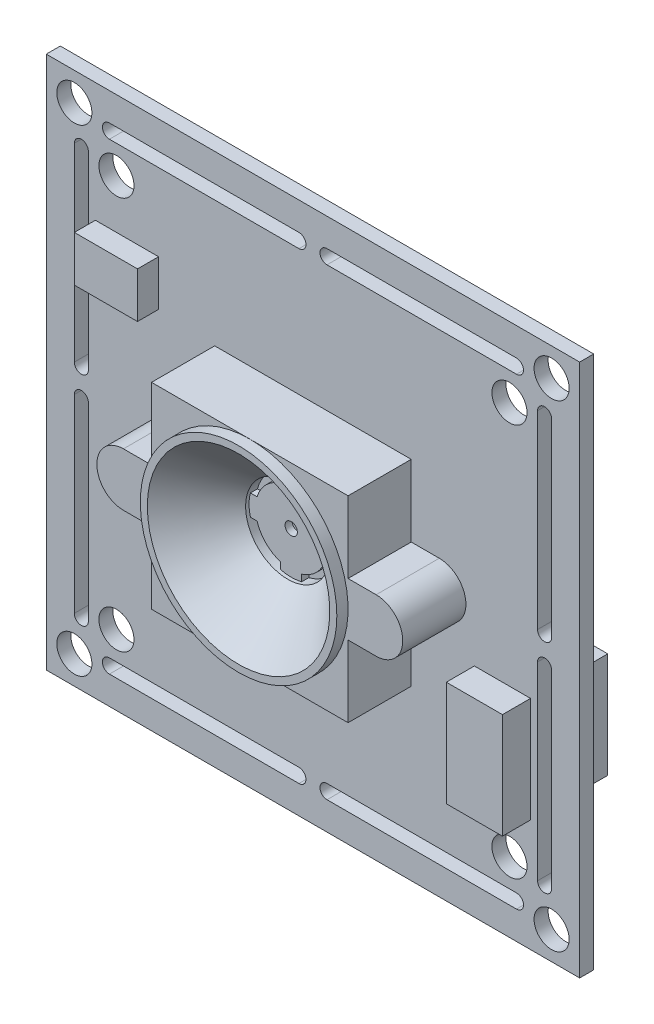
SolidWorks part; units mm, degrees
ref_plane "Front Plane" through (0, 0, 0) normal (0, 0, 1) x (1, 0, 0)
ref_plane "Top Plane" through (0, 0, 0) normal (0, 1, 0) x (1, 0, 0)
ref_plane "Right Plane" through (0, 0, 0) normal (1, 0, 0) x (0, 0, -1)
sketch "ｽｹｯﾁ1" plane through (0, 0, 0) normal (0, 0, 1) x (1, 0, 0)
  line L0 (1, 16.5) -> (14.5, 16.5) construction
  line L1 (-19, -19) -> (19, -19)
  line L2 (-19, -19) -> (-19, 19)
  line L3 (-19, 19) -> (19, 19)
  line L4 (19, -19) -> (19, 19)
  line L5 (-19, -19) -> (19, 19) construction
  line L6 (-19, 19) -> (19, -19) construction
  line L7 (1, 17) -> (14.5, 17)
  line L8 (1, 16) -> (14.5, 16)
  line L9 (0, 0) -> (0, 25.3594) construction
  line L10 (-1, 16.5) -> (-14.5, 16.5) construction
  line L11 (-1, 17) -> (-14.5, 17)
  line L12 (-1, 16) -> (-14.5, 16)
  line L13 (16.5, -1) -> (16.5, -14.5) construction
  line L14 (17, -1) -> (17, -14.5)
  line L15 (16, -1) -> (16, -14.5)
  line L16 (16.5, 1) -> (16.5, 14.5) construction
  line L17 (17, 1) -> (17, 14.5)
  line L18 (16, 1) -> (16, 14.5)
  line L19 (-1, -16.5) -> (-14.5, -16.5) construction
  line L20 (-1, -17) -> (-14.5, -17)
  line L21 (-1, -16) -> (-14.5, -16)
  line L22 (1, -16.5) -> (14.5, -16.5) construction
  line L23 (1, -17) -> (14.5, -17)
  line L24 (1, -16) -> (14.5, -16)
  line L25 (-16.5, 1) -> (-16.5, 14.5) construction
  line L26 (-17, 1) -> (-17, 14.5)
  line L27 (-16, 1) -> (-16, 14.5)
  line L28 (-16.5, -1) -> (-16.5, -14.5) construction
  line L29 (-17, -1) -> (-17, -14.5)
  line L30 (-16, -1) -> (-16, -14.5)
  circle A0 centre (17, 17) radius 1.25
  circle A1 centre (14, 14) radius 1.25
  arc A2 (1, 17) -> (1, 16) centre (1, 16.5) ccw
  arc A3 (14.5, 16) -> (14.5, 17) centre (14.5, 16.5) ccw
  arc A6 (-1, 17) -> (-1, 16) centre (-1, 16.5) cw
  arc A7 (-14.5, 16) -> (-14.5, 17) centre (-14.5, 16.5) cw
  circle A8 centre (17, -17) radius 1.25
  circle A9 centre (14, -14) radius 1.25
  arc A10 (17, -1) -> (16, -1) centre (16.5, -1) ccw
  arc A11 (16, -14.5) -> (17, -14.5) centre (16.5, -14.5) ccw
  arc A12 (17, 1) -> (16, 1) centre (16.5, 1) cw
  arc A13 (16, 14.5) -> (17, 14.5) centre (16.5, 14.5) cw
  circle A14 centre (-17, -17) radius 1.25
  circle A15 centre (-14, -14) radius 1.25
  arc A16 (-1, -17) -> (-1, -16) centre (-1, -16.5) ccw
  arc A17 (-14.5, -16) -> (-14.5, -17) centre (-14.5, -16.5) ccw
  arc A18 (1, -17) -> (1, -16) centre (1, -16.5) cw
  arc A19 (14.5, -16) -> (14.5, -17) centre (14.5, -16.5) cw
  circle A20 centre (-17, 17) radius 1.25
  circle A21 centre (-14, 14) radius 1.25
  arc A22 (-17, 1) -> (-16, 1) centre (-16.5, 1) ccw
  arc A23 (-16, 14.5) -> (-17, 14.5) centre (-16.5, 14.5) ccw
  arc A24 (-17, -1) -> (-16, -1) centre (-16.5, -1) cw
  arc A25 (-16, -14.5) -> (-17, -14.5) centre (-16.5, -14.5) cw
  point P0 (0, 0)
  point P10 (7.75, 16.5)
  point P19 (-28.6348, 16.5)
  point P20 (0, 0)
  point P25 (-7.75, 16.5)
  point P33 (16.5, -7.75)
  point P42 (16.5, 7.75)
  point P51 (-7.75, -16.5)
  point P60 (7.75, -16.5)
  point P69 (-16.5, 7.75)
  point P78 (-16.5, -7.75)
  point P83 (0, 0)
  dimension "D2" = 2.5
  dimension "D3" = 2
  dimension "D8" = 0.5
  dimension "D1" = 38
  dimension "D4" = 5
  dimension "D5" = 4.5
  dimension "D6" = 2.5
  dimension "D7" = 2
  dimension "D9" = 4
extrude "ﾎﾞｽ - 押し出し1" add sketch "ｽｹｯﾁ1" along normal blind 1
sketch "ｽｹｯﾁ2" plane through (0, 0, 1) normal (0, 0, 1) x (1, 0, 0)
  line L0 (0, 0) -> (22.7592, 0) construction
  line L1 (-7, -7) -> (7, -7)
  line L2 (-7, -7) -> (-7, -1.8966)
  line L3 (-7, 7) -> (7, 7)
  line L4 (7, -7) -> (7, -1.8966)
  line L5 (-7, -7) -> (7, 7) construction
  line L6 (-7, 7) -> (7, -7) construction
  line L7 (9, 1.8966) -> (7, 1.8966)
  line L8 (9, -1.8966) -> (7, -1.8966)
  line L9 (7, 1.8966) -> (7, 7)
  line L10 (0, 0) -> (0, 14.0788) construction
  line L11 (-9, -1.8966) -> (-7, -1.8966)
  line L12 (-9, 1.8966) -> (-7, 1.8966)
  line L13 (-7, 1.8966) -> (-7, 7)
  arc A0 (9, -1.8966) -> (9, 1.8966) centre (9, 0) ccw
  arc A1 (-9, -1.8966) -> (-9, 1.8966) centre (-9, 0) cw
  point P0 (0, 0)
  point P9 (0, 0)
  dimension "D1" = 3.7932
  dimension "D2" = 18
  dimension "D3" = 14
  dimension "D4" = 14
extrude "ﾎﾞｽ - 押し出し2" add sketch "ｽｹｯﾁ2" along normal blind 4.5
sketch "ｽｹｯﾁ3" plane through (0, 0, 5.5) normal (0, 0, 1) x (1, 0, 0)
  line L0 (7, 7) -> (-7, 7) construction
  circle A0 centre (0, 0) radius 7
extrude "ﾎﾞｽ - 押し出し3" add sketch "ｽｹｯﾁ3" along normal blind 0.8
sketch "ｽｹｯﾁ4" plane through (0, 0, 0) normal (0, 1, 0) x (1, 0, 0)
  line L0 (0, 0) -> (0, -9.9697) construction
  line L1 (-6.5, -6.3) -> (-3, -2.8)
  line L2 (-7, -6.3) -> (7, -6.3) construction
  line L3 (-3, -2.8) -> (-3, -2.55)
  line L4 (-3, -2.55) -> (0, -2.55)
  line L5 (0, -2.55) -> (0, -6.3)
  line L6 (0, -6.3) -> (-6.5, -6.3)
  line L7 (-7, -5.5) -> (-7, -6.3) construction
  line L8 (-7, -5.5) -> (-7, -1) construction
  dimension "D1" = 0.5
  dimension "D2" = 45
  dimension "D3" = 0.25
  dimension "D4" = 6
revolve "ｶｯﾄ - 回転1" cut sketch "ｽｹｯﾁ4" angle 360 about L0
sketch "ｽｹｯﾁ5" plane through (0, 0, 2.55) normal (0, 0, 1) x (1, 0, 0)
  line L0 (0.75, 2.9047) -> (0.75, 2.4316)
  line L1 (2.4316, 0.75) -> (2.9047, 0.75)
  line L2 (3.5051, 0) -> (0, 0) construction
  line L3 (0, 0) -> (0, 3.9194) construction
  line L4 (2.9047, -0.75) -> (2.4316, -0.75)
  line L5 (0.75, -2.4316) -> (0.75, -2.9047)
  line L6 (-0.75, -2.9047) -> (-0.75, -2.4316)
  line L7 (-2.4316, -0.75) -> (-2.9047, -0.75)
  line L8 (-2.9047, 0.75) -> (-2.4316, 0.75)
  line L9 (-0.75, 2.4316) -> (-0.75, 2.9047)
  circle A0 centre (0, 0) radius 0.4389
  circle A1 centre (0, 0) radius 3 construction
  arc A2 (2.4316, 0.75) -> (0.75, 2.4316) centre (0, 0) ccw
  arc A3 (2.9047, 0.75) -> (0.75, 2.9047) centre (0, 0) ccw
  arc A4 (0.75, -2.4316) -> (2.4316, -0.75) centre (0, 0) ccw
  arc A5 (0.75, -2.9047) -> (2.9047, -0.75) centre (0, 0) ccw
  arc A6 (-2.4316, -0.75) -> (-0.75, -2.4316) centre (0, 0) ccw
  arc A7 (-2.9047, -0.75) -> (-0.75, -2.9047) centre (0, 0) ccw
  arc A8 (-0.75, 2.4316) -> (-2.4316, 0.75) centre (0, 0) ccw
  arc A9 (-0.75, 2.9047) -> (-2.9047, 0.75) centre (0, 0) ccw
  point P26 (0, 0)
  dimension "D1" = 0.8779
  dimension "D2" = 5.0892
  dimension "D3" = 1.5
  dimension "D4" = 1.5
  dimension "D5" = 4
extrude "ｶｯﾄ - 押し出し1" cut sketch "ｽｹｯﾁ5" against normal blind 0.5
sketch "ｽｹｯﾁ6" plane through (0, 0, 0) normal (0, 0, -1) x (-1, 0, 0)
  line L0 (0, -9.0299) -> (0, 12.1397) construction
  line L1 (6.1616, 13.2297) -> (-6.1616, 13.2297)
  line L2 (6.1616, 13.2297) -> (6.1616, -9.0299)
  line L3 (6.1616, -9.0299) -> (-6.1616, -9.0299)
  line L4 (-6.1616, 13.2297) -> (-6.1616, -9.0299)
  point P5 (0, 12.1397)
extrude "ﾎﾞｽ - 押し出し4" add sketch "ｽｹｯﾁ6" along normal blind 3
sketch "ｽｹｯﾁ7" plane through (0, 0, 0) normal (0, 0, -1) x (-1, 0, 0)
  line L0 (19, -19) -> (-19, -19) construction
  line L1 (-11.5, -3.5) -> (-15.5, -3.5)
  line L2 (-11.5, -3.5) -> (-11.5, -11)
  line L3 (-11.5, -11) -> (-15.5, -11)
  line L4 (-15.5, -3.5) -> (-15.5, -11)
  line L5 (-11.5, -3.5) -> (-15.5, -11) construction
  line L6 (-11.5, -11) -> (-15.5, -3.5) construction
  line L7 (-19, -19) -> (-19, 19) construction
  point P0 (-13.5, -7.25)
  dimension "D1" = 8
  dimension "D2" = 3.5
  dimension "D3" = 4
  dimension "D4" = 7.5
extrude "ﾎﾞｽ - 押し出し5" add sketch "ｽｹｯﾁ7" along normal blind 4.5
sketch "ｽｹｯﾁ9" plane through (0, 0, 1) normal (0, 0, 1) x (1, 0, 0)
  line L0 (-16, 1) -> (-16, 14.5) construction
  line L1 (-15.5, 10.5) -> (-11, 10.5)
  line L2 (-15.5, 10.5) -> (-15.5, 7.25)
  line L3 (-15.5, 7.25) -> (-11, 7.25)
  line L4 (-11, 10.5) -> (-11, 7.25)
  line L5 (-15.5, 10.5) -> (-11, 7.25) construction
  line L6 (-15.5, 7.25) -> (-11, 10.5) construction
  line L7 (19, 19) -> (-19, 19) construction
  point P4 (-13.25, 8.875)
  dimension "D1" = 0.5
  dimension "D2" = 4.5
  dimension "D3" = 3.25
  dimension "D4" = 8.5
extrude "ﾎﾞｽ - 押し出し6" add sketch "ｽｹｯﾁ9" along normal blind 1.5
sketch "ｽｹｯﾁ10" plane through (0, 0, 1) normal (0, 0, 1) x (1, 0, 0)
  line L4 (15.5, -11) -> (15.5, -3.5)
  line L5 (11.5, -11) -> (15.5, -11)
  line L6 (11.5, -3.5) -> (11.5, -11)
  line L7 (15.5, -3.5) -> (11.5, -3.5)
  line L8 (15.5, -11) -> (15.5, -3.5)
  line L9 (11.5, -11) -> (15.5, -11)
  line L10 (11.5, -3.5) -> (11.5, -11)
  line L11 (15.5, -3.5) -> (11.5, -3.5)
  dimension "D1" = 0
extrude "ﾎﾞｽ - 押し出し7" add sketch "ｽｹｯﾁ10" along normal blind 2
